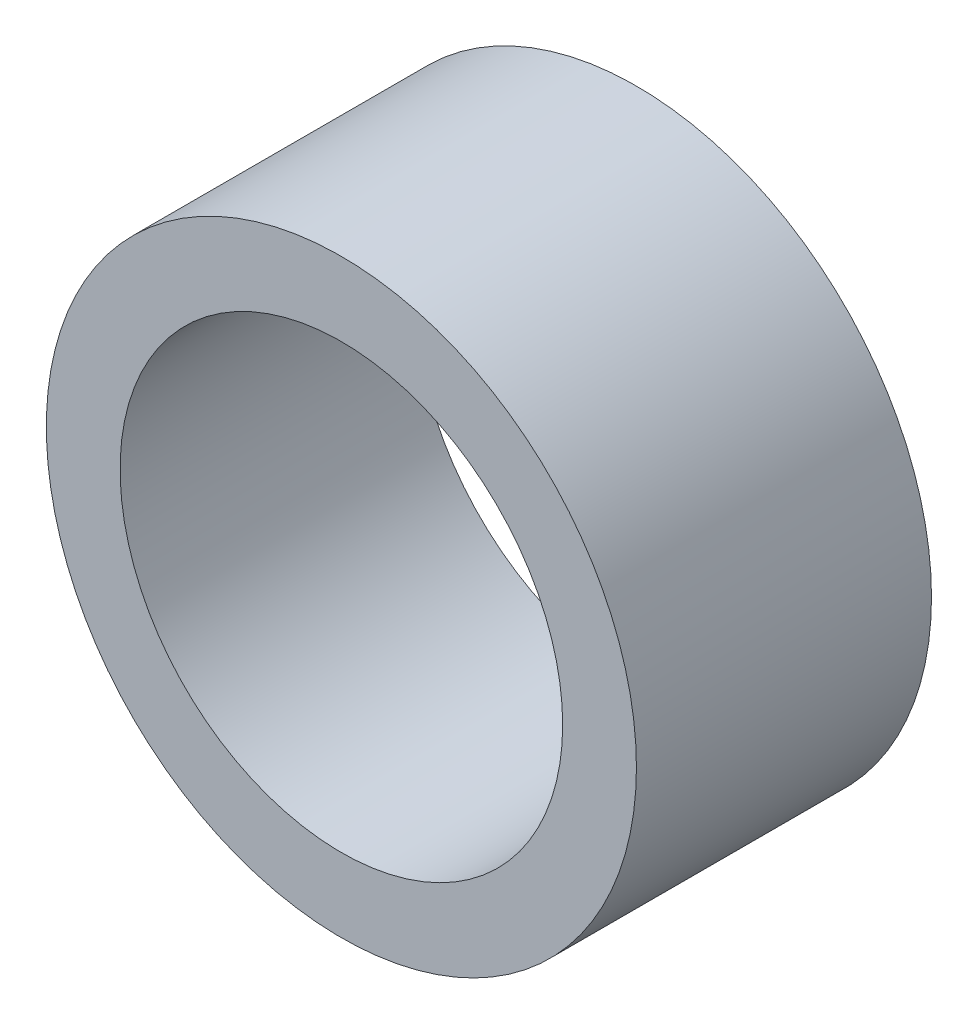
SolidWorks part; units mm, degrees
material "AISI 1020"
ref_plane "Ön Düzlem" through (0, 0, 0) normal (0, 0, 1) x (1, 0, 0)
ref_plane "Üst Düzlem" through (0, 0, 0) normal (0, 1, 0) x (1, 0, 0)
ref_plane "Sağ Düzlem" through (0, 0, 0) normal (1, 0, 0) x (0, 0, -1)
sketch "Çizim1" plane through (0, 0, 0) normal (0, 0, 1) x (1, 0, 0)
  circle A0 centre (0, 0) radius 40
  circle A1 centre (0, 0) radius 30
  dimension "D1" = 60
  dimension "D2" = 80
extrude "Yükseklik-Ekstrüzyon1" add sketch "Çizim1" along normal blind 40
